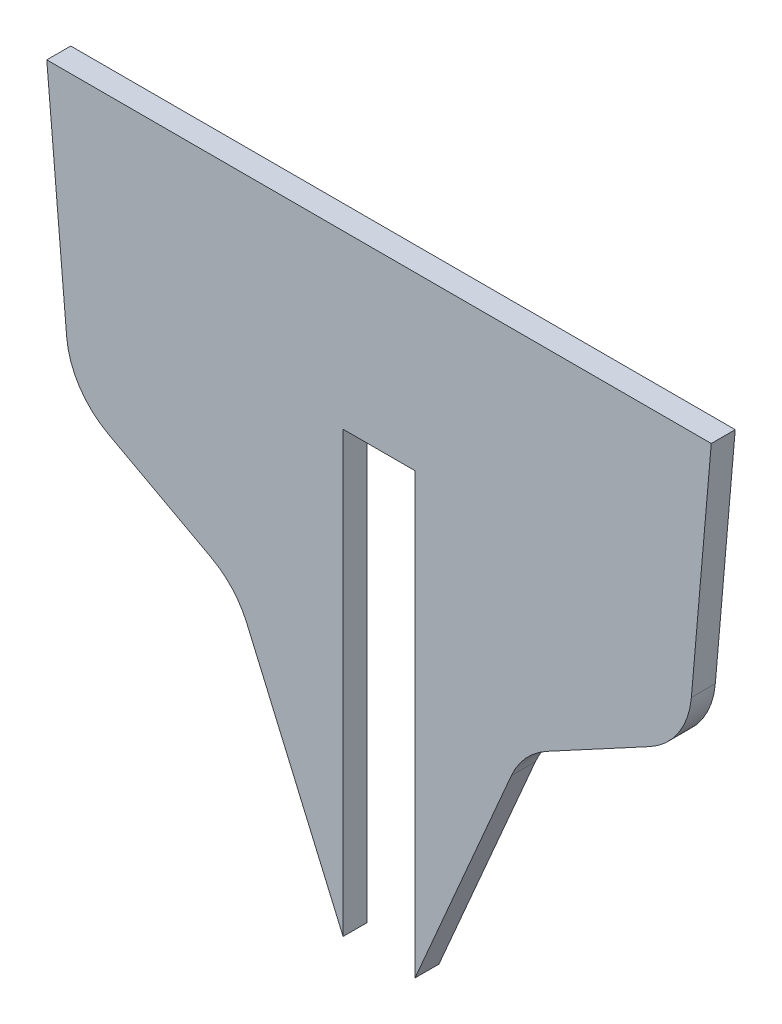
SolidWorks part; units mm, degrees
ref_plane "Plan de face" through (0, 0, 0) normal (0, 0, 1) x (1, 0, 0)
ref_plane "Plan de dessus" through (0, 0, 0) normal (0, 1, 0) x (1, 0, 0)
ref_plane "Plan de droite" through (0, 0, 0) normal (1, 0, 0) x (0, 0, -1)
sketch "Esquisse1" plane through (0, 0, 0) normal (0, 0, 1) x (1, 0, 0)
  line L5 (11.9172, -65.8529) -> (11.9172, -10.8529)
  line L6 (11.9172, -10.8529) -> (2.9172, -10.8529)
  line L7 (7.4172, -10.8529) -> (7.4172, 12.6243) construction
  line L8 (2.9172, -65.8529) -> (2.9172, -10.8529)
  line L19 (-34.1783, 10.6471) -> (49.0127, 10.6471)
  line L20 (11.9172, -65.8529) -> (25.366, -34.6758)
  line L21 (25.366, -34.6758) -> (46.0569, -23.5093)
  line L22 (46.0569, -23.5093) -> (49.0127, 10.6471)
  line L23 (-31.2225, -23.5093) -> (-34.1783, 10.6471)
  line L24 (-10.5316, -34.6758) -> (-31.2225, -23.5093)
  line L25 (2.9172, -65.8529) -> (-10.5316, -34.6758)
  point P10 (7.4172, 10.6471)
  point P12 (54.9244, 11.9608)
  point P13 (7.4172, 10.6471)
  point P14 (46.0569, -23.5093)
  point P15 (25.366, -34.6758)
  point P16 (49.0127, 10.6471)
  dimension "D1" = 21.5
  dimension "D5" = 9
  dimension "D7" = 55
extrude "Boss.-Extru.1" add sketch "Esquisse1" along normal blind 3
fillet "Congé1" radius 10 4 edges at (46.0569, -23.5093, 1.5) (25.366, -34.6758, 1.5) (-31.2225, -23.5093, 1.5) (-10.5316, -34.6758, 1.5)
